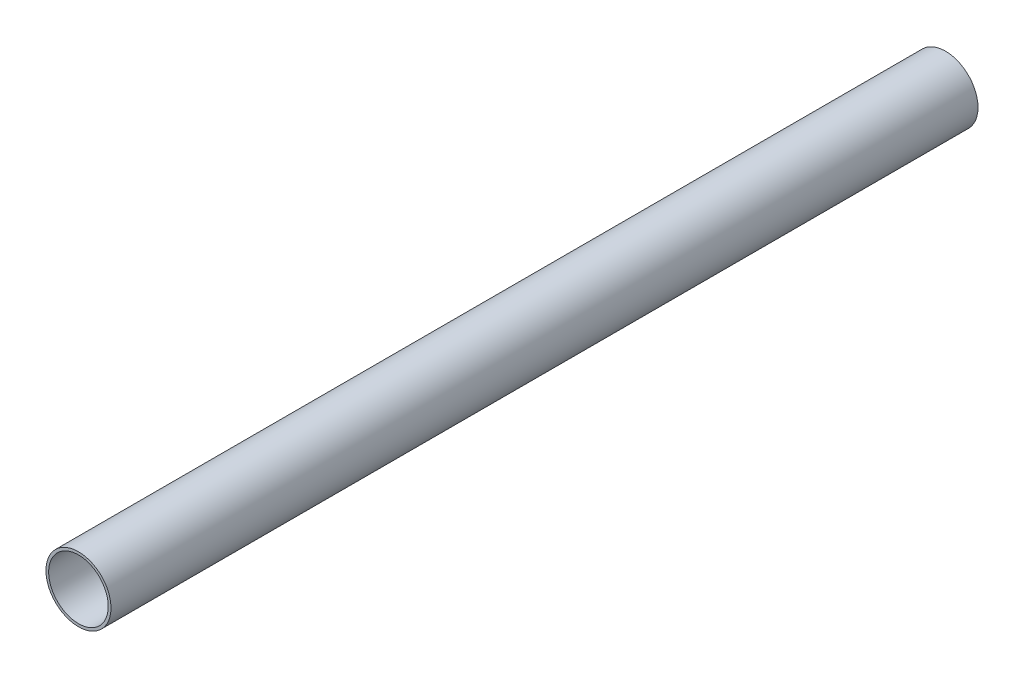
SolidWorks part; units mm, degrees
material "Karbon Fiber Boru "
ref_plane "Ön Düzlem" through (0, 0, 0) normal (0, 0, 1) x (1, 0, 0)
ref_plane "Üst Düzlem" through (0, 0, 0) normal (0, 1, 0) x (1, 0, 0)
ref_plane "Sağ Düzlem" through (0, 0, 0) normal (1, 0, 0) x (0, 0, -1)
sketch "Çizim1" plane through (0, 0, 0) normal (0, 0, 1) x (1, 0, 0)
  circle A0 centre (0, 0) radius 12
  circle A1 centre (0, 0) radius 11
  dimension "D1" = 24
  dimension "D2" = 22
extrude "Yükseklik-Ekstrüzyon1" add sketch "Çizim1" along normal blind 320
